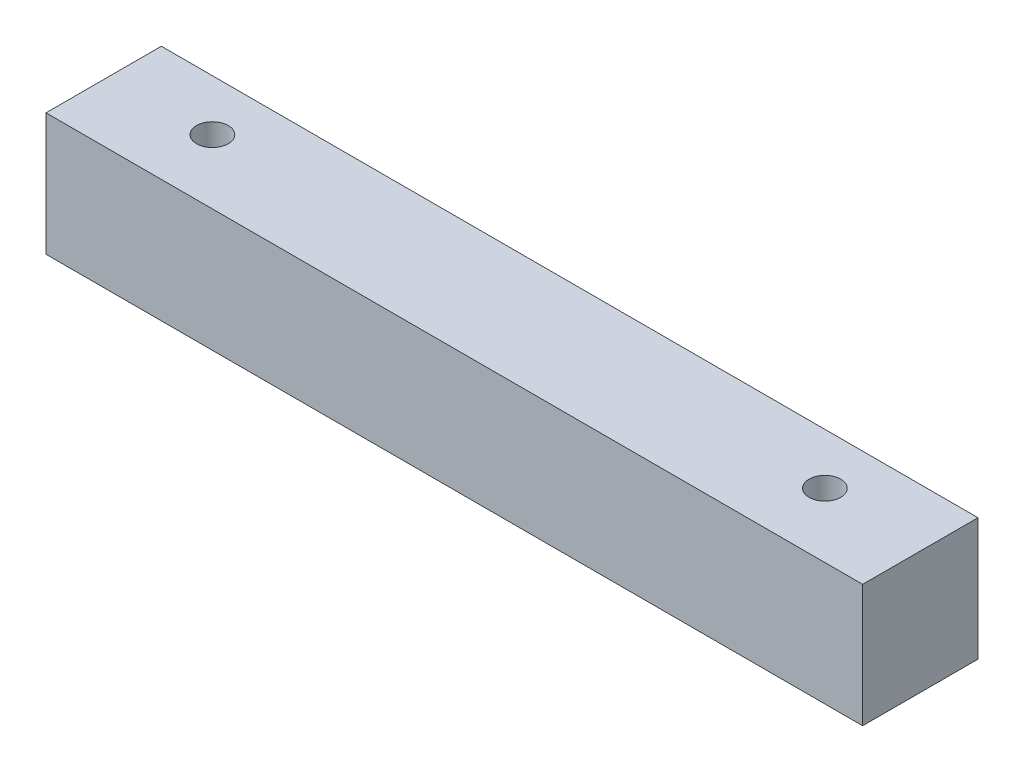
SolidWorks part; units mm, degrees
ref_plane "前视基准面" through (0, 0, 0) normal (0, 0, 1) x (1, 0, 0)
ref_plane "上视基准面" through (0, 0, 0) normal (0, 1, 0) x (1, 0, 0)
ref_plane "右视基准面" through (0, 0, 0) normal (1, 0, 0) x (0, 0, -1)
other "Configuration Table"
sketch "草图1" plane through (0, 0, 0) normal (0, 0, 1) x (1, 0, 0)
  line L1 (0, 0) -> (80, 0)
  line L2 (0, 0) -> (0, 12)
  line L3 (0, 12) -> (80, 12)
  line L4 (80, 0) -> (80, 12)
  dimension "D1" = 80
  dimension "D2" = 12
extrude "凸台-拉伸1" add sketch "草图1" along normal blind 11.5
sketch "草图2" plane through (0, 12, 0) normal (0, 1, 0) x (1, 0, 0)
  line L0 (40, 0) -> (40, -9.3606) construction
  line L1 (80, 0) -> (0, 0) construction
  circle A0 centre (10, -5) radius 1.55
  circle A1 centre (70, -5) radius 1.55
  dimension "D1" = 3.1
  dimension "D2" = 5
  dimension "D3" = 30
extrude "切除-拉伸1" cut sketch "草图2" against normal up to next
sketch "草图3" plane through (0, 0, 11.5) normal (0, 0, 1) x (1, 0, 0)
  line L4 (0, 12) -> (0, 0)
  line L5 (0, 0) -> (80, 0)
  line L6 (80, 0) -> (80, 12)
  line L7 (80, 12) -> (0, 12)
  line L8 (0, 12) -> (0, 0)
  line L9 (0, 0) -> (80, 0)
  line L10 (80, 0) -> (80, 12)
  line L11 (80, 12) -> (0, 12)
  dimension "D1" = 0
extrude "切除-拉伸2" cut sketch "草图3" against normal blind 0.2
